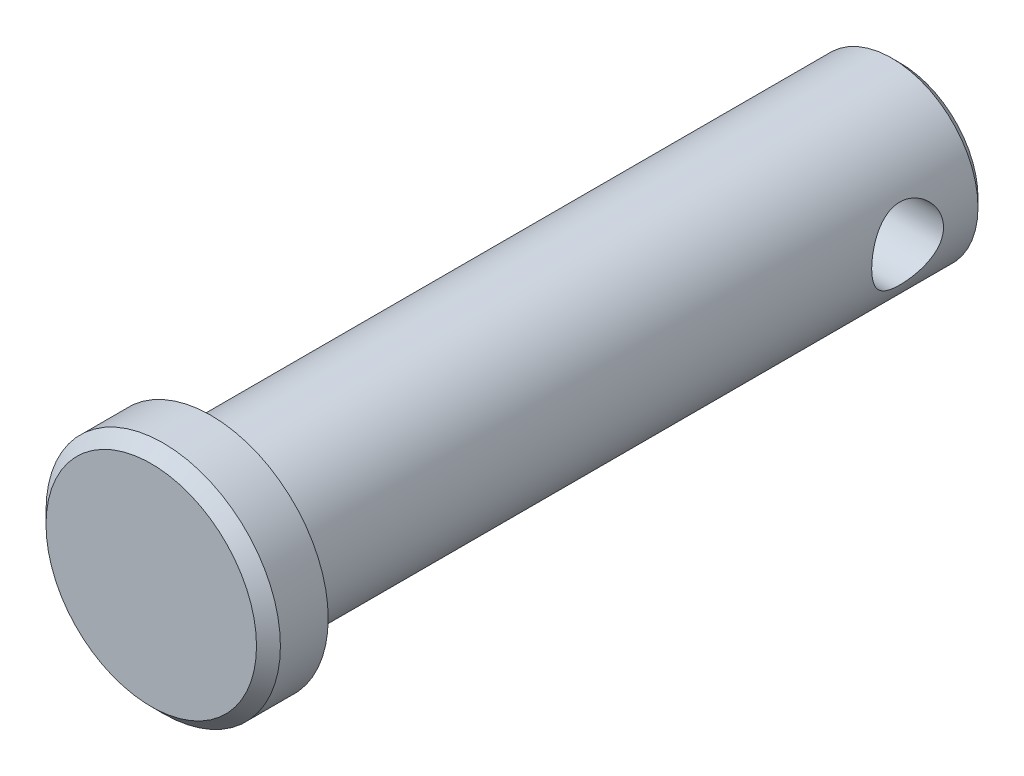
SolidWorks part; units mm, degrees
ref_plane "Front" through (0, 0, 0) normal (0, 0, 1) x (1, 0, 0)
ref_plane "Top" through (0, 0, 0) normal (0, 1, 0) x (1, 0, 0)
ref_plane "Right" through (0, 0, 0) normal (1, 0, 0) x (0, 0, -1)
sketch "Sketch1" plane through (0, 0, 0) normal (0, 0, 1) x (1, 0, 0)
  circle A0 centre (0, 0) radius 4.7625
  point P3 (0, 4.7625)
  point P4 (0, -4.7625)
  dimension "dia" = 9.525
extrude "Extrude1" add sketch "Sketch1" along normal mid plane 38.1
sketch "Sketch2" plane through (0, 0, 19.05) normal (0, 0, 1) x (1, 0, 0)
  circle A0 centre (0, 0) radius 6.477
  dimension "head dia" = 12.954
extrude "Extrude2" add sketch "Sketch2" along normal blind 3.302
chamfer "Chamfer1" distance 0.6604 angle 45 1 edges at (6.477, 0, 22.352)
sketch "Sketch3" plane through (0, 0, 0) normal (1, 0, 0) x (0, 0, -1)
  line L0 (-19.05, -4.7625) -> (-19.05, 4.7625) construction
  circle A0 centre (14.6844, 0) radius 1.9844
  point P2 (12.7, 0)
  dimension "hole dia" = 3.9688
  dimension "useable Lg" = 31.75
extrude "Extrude3" cut sketch "Sketch3" against normal through all and the other way through all
chamfer "Chamfer2" distance 0.4763 angle 45 1 edges at (4.7625, 0, -19.05)
ref_plane "Plane1" through (0, 0, -14.6844) normal (0, 0, 1) x (1, 0, 0)
sketch "Sketch8" plane through (0, 0, 0) normal (1, 0, 0) x (0, 0, -1)
  line L0 (-22.352, 5.8166) -> (-22.352, -5.8166) construction
  line L1 (-21.6916, -6.477) -> (-19.05, -6.477) construction
  line L2 (19.05, -4.2862) -> (19.05, 4.2862) construction
  point P0 (-22.352, 6.477)
  point P1 (-19.05, 6.477)
  point P5 (19.05, 4.7625)
  point P8 (-22.352, -6.477)
  point P9 (19.05, -4.7625)
equation "\"D1@Chamfer1\" = \"head ht@Extrude2\" * .2"
equation "\"D1@Chamfer2\" = \"dia@Sketch1\" * .05"
